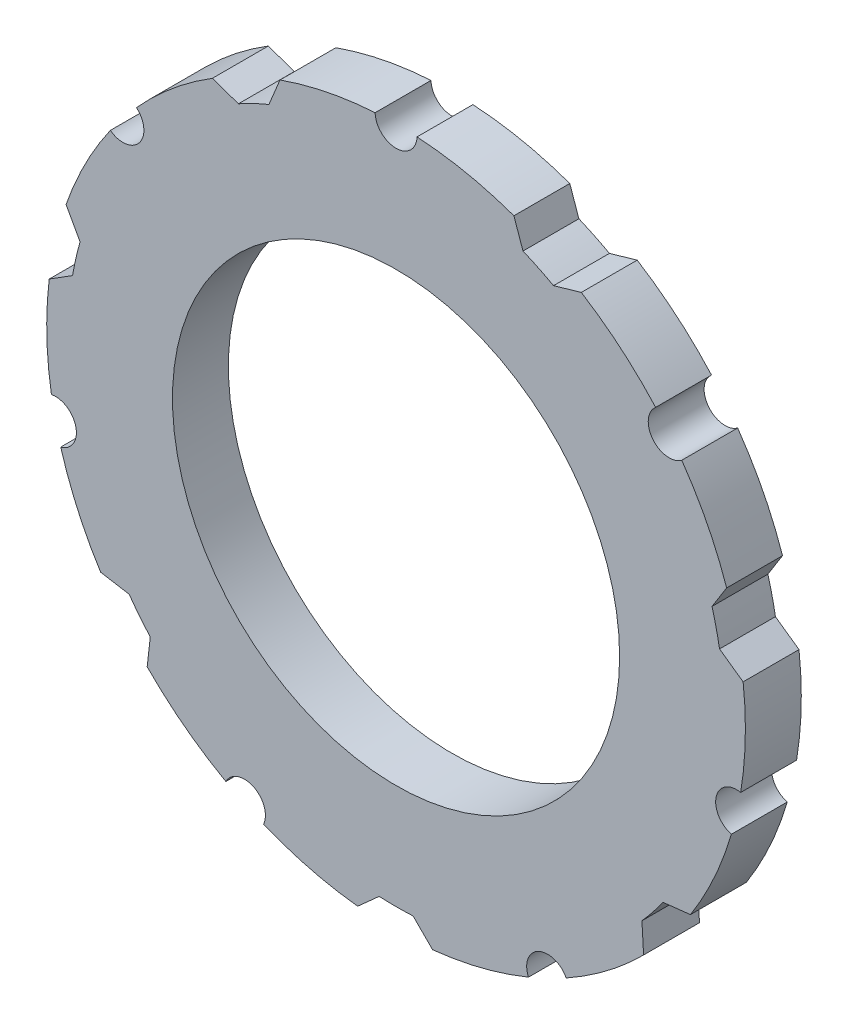
SolidWorks part; units mm, degrees
ref_plane "Front Plane" through (0, 0, 0) normal (0, 0, 1) x (1, 0, 0)
ref_plane "Top Plane" through (0, 0, 0) normal (0, 1, 0) x (1, 0, 0)
ref_plane "Right Plane" through (0, 0, 0) normal (1, 0, 0) x (0, 0, -1)
sketch "Sketch1" plane through (0, 0, 0) normal (0, 0, 1) x (1, 0, 0)
  line L0 (24.8369, 2.8506) -> (23.1491, 4.0456)
  line L1 (8.4334, 23.5346) -> (9.0848, 21.6729)
  line L2 (23.6582, 8.0801) -> (22.6089, 6.4101)
  line L3 (13.2569, 21.1957) -> (11.2703, 20.6211)
  line L4 (17.7143, -17.641) -> (17.5962, -15.5763)
  line L5 (21.0679, -13.4589) -> (19.108, -13.6797)
  line L6 (-2.7476, -24.8486) -> (-1.207, -23.469)
  line L7 (2.6131, -24.8631) -> (1.2184, -23.4684)
  line L8 (-21.1405, -13.3447) -> (-19.1013, -13.689)
  line L9 (-17.8095, -17.5448) -> (-17.5887, -15.5849)
  line L10 (-23.6142, 8.208) -> (-22.612, 6.3991)
  line L11 (-24.8212, 2.985) -> (-23.1511, 4.0344)
  line L12 (-8.3059, 23.5799) -> (-9.0954, 21.6685)
  line L13 (-13.142, 21.2671) -> (-11.2803, 20.6157)
  circle A0 centre (0, 0) radius 16
  arc A1 (11.2703, 20.6211) -> (9.0848, 21.6729) centre (0, 0) ccw
  arc A2 (-1.4993, 24.955) -> (-8.3059, 23.5799) centre (0, 0) ccw
  arc A3 (-1.4993, 24.955) -> (1.4993, 24.955) centre (0, 25) ccw
  arc A4 (-20.4454, 14.387) -> (-18.5758, 16.7314) centre (-19.5458, 15.5872) ccw
  arc A5 (-23.9957, -7.0147) -> (-24.663, -4.0913) centre (-24.3732, -5.563) ccw
  arc A6 (-9.4767, -23.1342) -> (-12.1784, -21.8331) centre (-10.8471, -22.5242) ccw
  arc A7 (12.1784, -21.8331) -> (9.4767, -23.1342) centre (10.8471, -22.5242) ccw
  arc A8 (24.663, -4.0913) -> (23.9957, -7.0147) centre (24.3732, -5.563) ccw
  arc A9 (18.5758, 16.7314) -> (20.4454, 14.387) centre (19.5458, 15.5872) ccw
  arc A10 (18.5758, 16.7314) -> (13.2569, 21.1957) centre (0, 0) ccw
  arc A11 (24.663, -4.0913) -> (24.8369, 2.8506) centre (0, 0) ccw
  arc A12 (12.1784, -21.8331) -> (17.7143, -17.641) centre (0, 0) ccw
  arc A13 (-9.4767, -23.1342) -> (-2.7476, -24.8486) centre (0, 0) ccw
  arc A14 (-23.9957, -7.0147) -> (-21.1405, -13.3447) centre (0, 0) ccw
  arc A15 (-20.4454, 14.387) -> (-23.6142, 8.208) centre (0, 0) ccw
  arc A16 (8.4334, 23.5346) -> (1.4993, 24.955) centre (0, 0) ccw
  arc A17 (-24.8212, 2.985) -> (-24.663, -4.0913) centre (0, 0) ccw
  arc A18 (-17.8095, -17.5448) -> (-12.1784, -21.8331) centre (0, 0) ccw
  arc A19 (2.6131, -24.8631) -> (9.4767, -23.1342) centre (0, 0) ccw
  arc A20 (21.0679, -13.4589) -> (23.9957, -7.0147) centre (0, 0) ccw
  arc A21 (23.6582, 8.0801) -> (20.4454, 14.387) centre (0, 0) ccw
  arc A22 (-9.0954, 21.6685) -> (-11.2803, 20.6157) centre (0, 0) ccw
  arc A23 (-22.612, 6.3991) -> (-23.1511, 4.0344) centre (0, 0) ccw
  arc A24 (-13.142, 21.2671) -> (-18.5758, 16.7314) centre (0, 0) ccw
  arc A25 (-19.1013, -13.689) -> (-17.5887, -15.5849) centre (0, 0) ccw
  arc A26 (-1.207, -23.469) -> (1.2184, -23.4684) centre (0, 0) ccw
  arc A27 (17.5962, -15.5763) -> (19.108, -13.6797) centre (0, 0) ccw
  arc A28 (23.1491, 4.0456) -> (22.6089, 6.4101) centre (0, 0) ccw
  point P4 (11.2703, 20.6211)
  point P10 (10.8479, 22.5238)
  point P29 (0, 0)
  point P59 (0, 0)
  dimension "D1" = 32
  dimension "D2" = 50
  dimension "D3" = 47
  dimension "D5" = 7
  dimension "D4" = 7
extrude "Boss-Extrude1" add sketch "Sketch1" along normal blind 4
